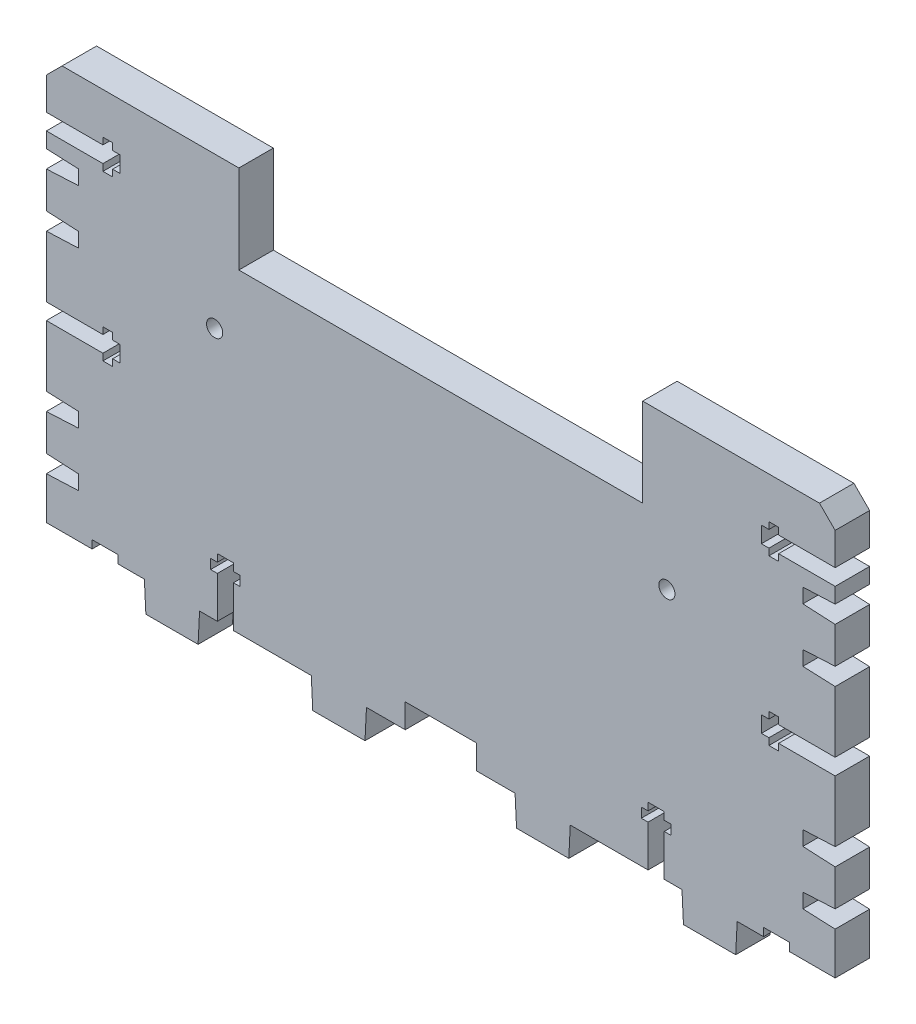
SolidWorks part; units mm, degrees
ref_plane "Front Plane" through (0, 0, 0) normal (0, 0, 1) x (1, 0, 0)
ref_plane "Top Plane" through (0, 0, 0) normal (0, 1, 0) x (1, 0, 0)
ref_plane "Right Plane" through (0, 0, 0) normal (1, 0, 0) x (0, 0, -1)
sketch "Sketch2" plane through (0, 0, 0) normal (0, 0, 1) x (1, 0, 0)
  line L0 (35.75, 58.5) -> (110.75, 58.5)
  line L1 (2.92, 74.92) -> (35.75, 74.92)
  line L2 (66.65, 4.5) -> (79.85, 4.5)
  line L3 (0, 0) -> (0, 7.8693)
  line L4 (6, 49.8307) -> (6, 57.1807) construction
  line L5 (6, 18.1693) -> (6, 20.8693)
  line L6 (0, 50.1307) -> (0, 56.8807)
  line L7 (0, 53.5057) -> (6, 53.5057) construction
  line L8 (6, 59.8807) -> (0, 60.1307)
  line L9 (0, 0) -> (8.5, 0)
  line L10 (18.2, 0) -> (28.45, 0) construction
  line L11 (6, 57.1807) -> (0, 56.8807)
  line L12 (6, 47.1307) -> (0, 46.8807)
  line L13 (6, 49.8307) -> (6, 57.1807) construction
  line L14 (6, 10.8193) -> (6, 8.1193)
  line L15 (6, 57.1807) -> (6, 59.8807)
  line L16 (6, 49.8307) -> (0, 50.1307)
  line L17 (0, 21.1193) -> (0, 32.4996)
  line L18 (0, 35.4993) -> (0, 46.8807)
  line L19 (0, 60.1307) -> (0, 62.9993)
  line L20 (146.5, 72) -> (143.58, 74.92)
  line L21 (0, 72) -> (0, 65.999)
  line L22 (0, 65.999) -> (10.5, 65.999)
  line L23 (6, 49.8307) -> (6, 47.1307)
  line L24 (6, 20.8693) -> (0, 21.1193)
  line L25 (6, 8.1193) -> (0, 7.8693)
  line L26 (140.5, 49.8307) -> (140.5, 57.1807) construction
  line L27 (113.2501, 0) -> (113.2501, 10.9) construction
  line L28 (111.7503, 0) -> (114.75, 0) construction
  line L29 (73.25, 58.5) -> (73.25, 4.5) construction
  line L30 (123.175, 0) -> (123.175, -5.5) construction
  line L31 (10.5, 31.2496) -> (10.5, 32.4996)
  line L32 (92.175, 0) -> (92.175, -5.5) construction
  line L33 (97.3, 0) -> (87.05, 0) construction
  line L34 (140.5, 49.8307) -> (140.5, 57.1807) construction
  line L35 (146.5, 53.5057) -> (140.5, 53.5057) construction
  line L36 (140.5, 49.8307) -> (140.5, 57.1807) construction
  line L37 (128.3, 0) -> (118.05, 0) construction
  line L38 (140.5, 49.8307) -> (140.5, 47.1307)
  line L39 (140.5, 49.8307) -> (146.5, 50.1307)
  line L40 (49.2, 0) -> (59.45, 0) construction
  line L41 (140.5, 57.1807) -> (140.5, 59.8807)
  line L42 (140.5, 47.1307) -> (146.5, 46.8807)
  line L43 (146.5, 21.1193) -> (146.5, 32.4996)
  line L44 (140.5, 57.1807) -> (146.5, 56.8807)
  line L45 (140.5, 59.8807) -> (146.5, 60.1307)
  line L46 (146.5, 0) -> (146.5, 7.8693)
  line L47 (49.475, -5.5) -> (49.2, 0)
  line L48 (35.75, 58.5) -> (35.75, 74.92)
  line L49 (0, 62.9993) -> (10.5, 62.9993)
  line L50 (12.3, 61.7493) -> (12.3, 62.9993)
  line L51 (10.5, 67.249) -> (12.3, 67.249)
  line L52 (12.3, 62.9993) -> (13.7, 62.9993)
  line L53 (12.3, 67.249) -> (12.3, 65.999)
  line L54 (13.7, 62.9993) -> (13.7, 65.999)
  line L55 (116, 9.5) -> (114.75, 9.5)
  line L56 (10.5, 61.7493) -> (10.5, 62.9993)
  line L57 (12.3, 65.999) -> (13.7, 65.999)
  line L58 (10.5, 61.7493) -> (12.3, 61.7493)
  line L59 (59.175, -5.5) -> (59.45, 0)
  line L60 (59.175, -5.5) -> (49.475, -5.5)
  line L61 (54.325, 0) -> (54.325, -5.5) construction
  line L62 (10.5, 67.249) -> (10.5, 65.999)
  line L63 (0, 32.4996) -> (10.5, 32.4996)
  line L64 (111.7503, 7.7) -> (111.7503, 0)
  line L65 (114.75, 9.5) -> (114.75, 10.9)
  line L66 (111.7503, 9.5) -> (111.7503, 10.9)
  line L67 (110.5003, 9.5) -> (111.7503, 9.5)
  line L68 (114.75, 0) -> (114.75, 7.7)
  line L69 (110.5003, 7.7) -> (111.7503, 7.7)
  line L70 (34.7497, 0) -> (49.2, 0)
  line L71 (59.45, 0) -> (66.65, 0)
  line L72 (116, 7.7) -> (114.75, 7.7)
  line L73 (116, 7.7) -> (116, 9.5)
  line L74 (110.5003, 7.7) -> (110.5003, 9.5)
  line L75 (111.7503, 10.9) -> (114.75, 10.9)
  line L76 (0, 35.4993) -> (10.5, 35.4993)
  line L77 (12.3, 35.4993) -> (13.7, 35.4993)
  line L78 (18.475, -5.5) -> (18.2, 0)
  line L79 (28.175, -5.5) -> (28.45, 0)
  line L80 (28.175, -5.5) -> (18.475, -5.5)
  line L81 (10.5, 36.7493) -> (10.5, 35.4993)
  line L82 (31.75, 0) -> (28.45, 0)
  line L83 (10.5, 31.2496) -> (12.3, 31.2496)
  line L84 (66.65, 0) -> (66.65, 4.5)
  line L85 (12.3, 36.7493) -> (12.3, 35.4993)
  line L86 (10.5, 36.7493) -> (12.3, 36.7493)
  line L87 (12.3, 32.4996) -> (13.7, 32.4996)
  line L88 (13.7, 32.4996) -> (13.7, 35.4993)
  line L89 (12.3, 31.2496) -> (12.3, 32.4996)
  line L90 (134.2, 31.2496) -> (134.2, 32.4996)
  line L91 (132.8, 32.4996) -> (132.8, 35.4993)
  line L92 (134.2, 32.4996) -> (132.8, 32.4996)
  line L93 (79.85, 0) -> (79.85, 4.5)
  line L94 (114.75, 0) -> (118.05, 0)
  line L95 (118.325, -5.5) -> (128.025, -5.5)
  line L96 (118.325, -5.5) -> (118.05, 0)
  line L97 (128.025, -5.5) -> (128.3, 0)
  line L98 (87.05, 0) -> (79.85, 0)
  line L99 (97.3, 0) -> (111.7503, 0)
  line L100 (87.325, -5.5) -> (97.025, -5.5)
  line L101 (87.325, -5.5) -> (87.05, 0)
  line L102 (136, 36.7493) -> (134.2, 36.7493)
  line L103 (134.2, 36.7493) -> (134.2, 35.4993)
  line L104 (136, 31.2496) -> (134.2, 31.2496)
  line L105 (136, 36.7493) -> (136, 35.4993)
  line L106 (134.2, 35.4993) -> (132.8, 35.4993)
  line L107 (146.5, 35.4993) -> (136, 35.4993)
  line L108 (146.5, 32.4996) -> (136, 32.4996)
  line L109 (110.75, 58.5) -> (110.75, 74.92)
  line L110 (97.025, -5.5) -> (97.3, 0)
  line L111 (23.325, 0) -> (23.325, -5.5) construction
  line L112 (146.5, 72) -> (146.5, 65.999)
  line L113 (136, 31.2496) -> (136, 32.4996)
  line L114 (146.5, 50.1307) -> (146.5, 56.8807)
  line L115 (140.5, 10.8193) -> (140.5, 18.1693) construction
  line L116 (140.5, 10.8193) -> (140.5, 18.1693) construction
  line L117 (146.5, 14.4943) -> (140.5, 14.4943) construction
  line L118 (140.5, 10.8193) -> (146.5, 11.1193)
  line L119 (136, 67.249) -> (136, 65.999)
  line L120 (136, 61.7493) -> (134.2, 61.7493)
  line L121 (134.2, 65.999) -> (132.8, 65.999)
  line L122 (136, 61.7493) -> (136, 62.9993)
  line L123 (146.5, 60.1307) -> (146.5, 62.9993)
  line L124 (133.2, 0) -> (133.2, 1.5)
  line L125 (34.7497, 10.9) -> (31.75, 10.9)
  line L126 (34.7497, 0) -> (31.75, 0) construction
  line L127 (33.2499, 0) -> (33.2499, 10.9) construction
  line L128 (35.9997, 7.7) -> (35.9997, 9.5)
  line L129 (30.5, 7.7) -> (30.5, 9.5)
  line L130 (30.5, 7.7) -> (31.75, 7.7)
  line L131 (35.9997, 7.7) -> (34.7497, 7.7)
  line L132 (31.75, 0) -> (31.75, 7.7)
  line L133 (35.9997, 9.5) -> (34.7497, 9.5)
  line L134 (34.7497, 9.5) -> (34.7497, 10.9)
  line L135 (31.75, 9.5) -> (31.75, 10.9)
  line L136 (34.7497, 7.7) -> (34.7497, 0)
  line L137 (6, 49.8307) -> (6, 57.1807) construction
  line L138 (146.5, 35.4993) -> (146.5, 46.8807)
  line L139 (146.5, 11.1193) -> (146.5, 17.8693)
  line L140 (140.5, 18.1693) -> (146.5, 17.8693)
  line L141 (132.8, 62.9993) -> (132.8, 65.999)
  line L142 (134.2, 67.249) -> (134.2, 65.999)
  line L143 (134.2, 62.9993) -> (132.8, 62.9993)
  line L144 (0, 14.4943) -> (6, 14.4943) construction
  line L145 (136, 67.249) -> (134.2, 67.249)
  line L146 (134.2, 61.7493) -> (134.2, 62.9993)
  line L147 (146.5, 62.9993) -> (136, 62.9993)
  line L148 (30.5, 9.5) -> (31.75, 9.5)
  line L149 (146.5, 65.999) -> (136, 65.999)
  line L150 (6, 10.8193) -> (6, 18.1693) construction
  line L151 (6, 18.1693) -> (0, 17.8693)
  line L152 (6, 10.8193) -> (6, 18.1693) construction
  line L153 (0, 11.1193) -> (0, 17.8693)
  line L154 (140.5, 8.1193) -> (146.5, 7.8693)
  line L155 (6, 10.8193) -> (0, 11.1193)
  line L156 (140.5, 20.8693) -> (146.5, 21.1193)
  line L157 (140.5, 10.8193) -> (140.5, 8.1193)
  line L158 (140.5, 18.1693) -> (140.5, 20.8693)
  line L159 (13.3, 0) -> (18.2, 0)
  line L160 (138, 1.5) -> (133.2, 1.5)
  line L161 (138, 0) -> (138, 1.5)
  line L162 (133.2, 0) -> (128.3, 0)
  line L163 (146.5, 0) -> (138, 0)
  line L165 (8.5, 0) -> (8.5, 1.5)
  line L166 (143.58, 74.92) -> (110.75, 74.92)
  line L167 (0, 72) -> (2.92, 74.92)
  line L168 (8.5, 1.5) -> (13.3, 1.5)
  line L169 (13.3, 0) -> (13.3, 1.5)
  circle A0 centre (31.25, 46.8664) radius 1.5
  circle A1 centre (115.25, 46.8664) radius 1.5
  point P90 (73.25, 4.6)
extrude "Boss-Extrude1" add sketch "Sketch2" along normal blind 6.4
